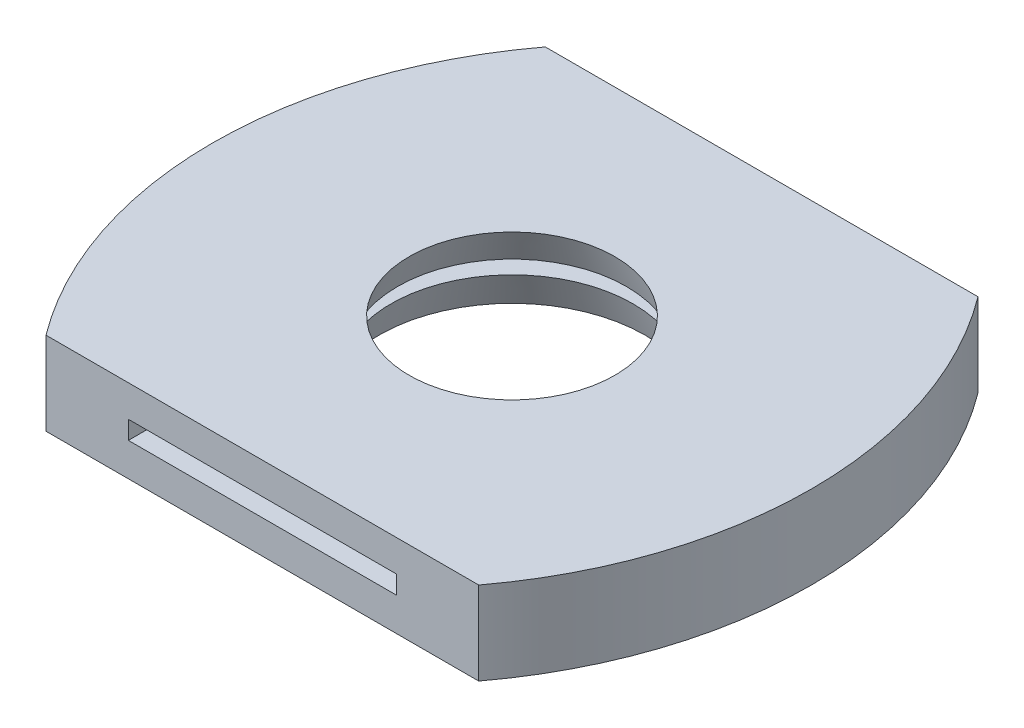
SolidWorks part; units mm, degrees
ref_plane "Front Plane" through (0, 0, 0) normal (0, 0, 1) x (1, 0, 0)
ref_plane "Top Plane" through (0, 0, 0) normal (0, 1, 0) x (1, 0, 0)
ref_plane "Right Plane" through (0, 0, 0) normal (1, 0, 0) x (0, 0, -1)
sketch "Lid case" plane through (0, 0, 0) normal (0, 1, 0) x (1, 0, 0)
  line L0 (-130, 150) -> (130, 150)
  line L1 (-130, -150) -> (130, -150)
  arc A0 (130, 150) -> (130, -150) centre (-70, 0) cw
  arc A1 (-130, 150) -> (-130, -150) centre (70, 0) ccw
  dimension "D6" = 250
  dimension "D7" = 250
  dimension "D1" = 260
  dimension "D2" = 130
  dimension "D3" = 150
  dimension "D4" = 150
  dimension "D5" = 130
extrude "Boss-Extrude1" add sketch "Lid case" along normal blind 50
ref_axis "Axis1" through (0, -54.3732, 0) along (0, 1, 0)
ref_plane "Plane1" through (0, 0, 0) normal (0, 0, 1) x (1, 0, 0)
sketch "Ventilation" plane through (0, 0, 0) normal (0, 0, 1) x (1, 0, 0)
  line L0 (0, 50) -> (0, 0)
  line L1 (0, 0) -> (-80, 0)
  line L2 (-80, 0) -> (-61.8015, 50)
  line L4 (0, -54.3732) -> (0, 100.2697) construction
  line L5 (-130, 0) -> (130, 0) construction
  line L6 (-61.8015, 50) -> (0, 50)
  line L7 (-130, 50) -> (130, 50) construction
  dimension "D2" = 80
  dimension "D3" = 70
revolve "Cut-Revolve1" cut sketch "Ventilation" angle 360 about axis through (0, -54.3732, 0) along (0, 1, 0)
sketch "Carbon filter hole" plane through (0, 0, 150) normal (0, 0, 1) x (1, 0, 0)
  line L0 (0, -54.3732) -> (0, 100.2697) construction
  line L1 (-80.5, 31) -> (80.5, 31)
  line L2 (-80.5, 31) -> (-80.5, 20)
  line L3 (-80.5, 20) -> (80.5, 20)
  line L4 (80.5, 31) -> (80.5, 20)
  line L6 (-130, 0) -> (130, 0) construction
  dimension "D1" = 161
  dimension "D2" = 11
  dimension "D3" = 80.5
  dimension "D4" = 20
extrude "Cut-Extrude3" cut sketch "Carbon filter hole" against normal blind 280
sketch "Sketch1" plane through (0, 0, 0) normal (0, -1, 0) x (1, 0, 0)
  line L0 (130, -150) -> (-130, -150) construction
  circle A0 centre (-110, -139) radius 3
  circle A1 centre (-82, -139) radius 3
  circle A2 centre (-54, -139) radius 3
  circle A3 centre (54, -139) radius 3
  circle A4 centre (82, -139) radius 3
  circle A5 centre (110, -139) radius 3
  dimension "D1" = 6
  dimension "D2" = 20
  dimension "D3" = 20
  dimension "D4" = 28
  dimension "D5" = 28
  dimension "D6" = 28
  dimension "D7" = 28
  dimension "D8" = 11
extrude "Cut-Extrude4" cut sketch "Sketch1" against normal blind 20
